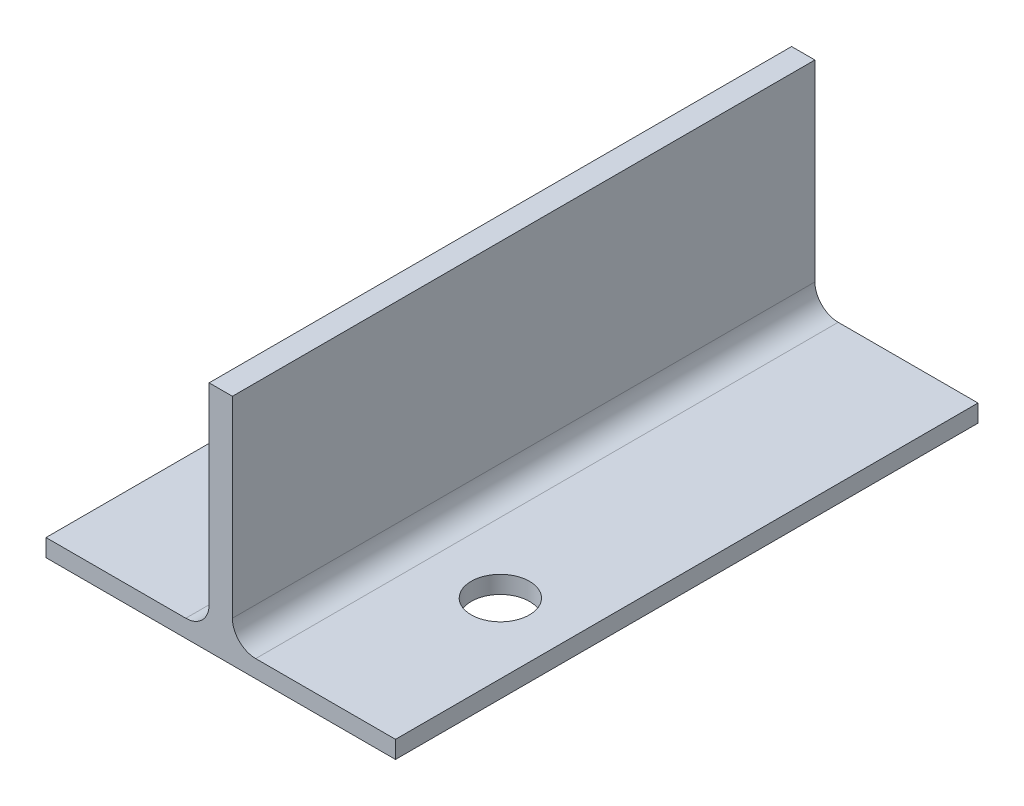
SolidWorks part; units mm, degrees
ref_plane "前视基准面" through (0, 0, 0) normal (0, 0, 1) x (1, 0, 0)
ref_plane "上视基准面" through (0, 0, 0) normal (0, 1, 0) x (1, 0, 0)
ref_plane "右视基准面" through (0, 0, 0) normal (1, 0, 0) x (0, 0, -1)
sketch "草图3" plane through (0, 0, 0) normal (0, 0, 1) x (1, 0, 0)
  line L0 (15, 1.5) -> (-15, 1.5)
  line L3 (-15, 1.5) -> (-15, 3)
  line L4 (-15, 3) -> (-3, 3)
  line L5 (-1, 5) -> (-1, 21.5)
  line L6 (-1, 21.5) -> (1, 21.5)
  line L7 (1, 21.5) -> (1, 5)
  line L9 (15, 3) -> (15, 1.5)
  line L10 (3, 3) -> (15, 3)
  arc A0 (-3, 3) -> (-1, 5) centre (-3, 5) ccw
  arc A1 (1, 5) -> (3, 3) centre (3, 5) ccw
  dimension "D1" = 2
  dimension "D2" = 2
extrude "凸台-拉伸3" add sketch "草图3" along normal mid plane 50
sketch "草图5" plane through (0, 3, 0) normal (0, 1, 0) x (1, 0, 0)
  circle A0 centre (9, -10) radius 2.5
  point P2 (0, 0)
extrude "切除-拉伸1" cut sketch "草图5" against normal through all
mirror "镜向1" about plane through (0, 0, 0) normal (1, 0, 0) of "切除-拉伸1"
